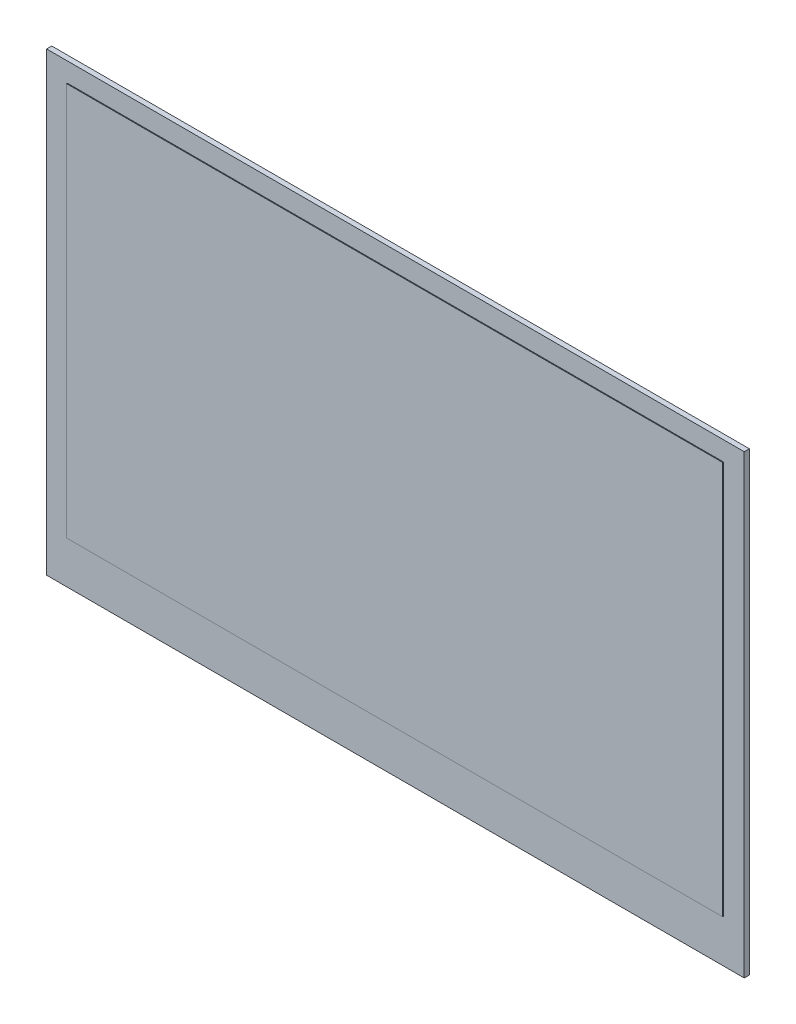
SolidWorks part; units mm, degrees
ref_plane "前视基准面" through (0, 0, 0) normal (0, 0, 1) x (1, 0, 0)
ref_plane "上视基准面" through (0, 0, 0) normal (0, 1, 0) x (1, 0, 0)
ref_plane "右视基准面" through (0, 0, 0) normal (1, 0, 0) x (0, 0, -1)
sketch "草图1" plane through (0, 0, 0) normal (0, 0, 1) x (1, 0, 0)
  line L1 (-85.1, 55.6) -> (85.1, 55.6)
  line L2 (-85.1, 55.6) -> (-85.1, -55.6)
  line L3 (-85.1, -55.6) -> (85.1, -55.6)
  line L4 (85.1, 55.6) -> (85.1, -55.6)
  line L5 (-85.1, 55.6) -> (85.1, -55.6) construction
  line L6 (-85.1, -55.6) -> (85.1, 55.6) construction
  point P0 (0, 0)
  dimension "D1" = 170.2
  dimension "D2" = 111.2
extrude "凸台-拉伸1" add sketch "草图1" along normal blind 1.25
sketch "草图2" plane through (0, 0, 1.25) normal (0, 0, 1) x (1, 0, 0)
  line L0 (85.1, 55.6) -> (-85.1, 55.6) construction
  line L1 (-80, 50.9) -> (80, 50.9)
  line L2 (-80, 50.9) -> (-80, -45.1)
  line L3 (-80, -45.1) -> (80, -45.1)
  line L4 (80, 50.9) -> (80, -45.1)
  line L5 (-80, 50.9) -> (80, -45.1) construction
  line L6 (-80, -45.1) -> (80, 50.9) construction
  point P0 (0, 2.9)
  dimension "D1" = 160
  dimension "D2" = 96
  dimension "D3" = 4.7
extrude "凸台-拉伸2" add sketch "草图2" along normal blind 0.2
